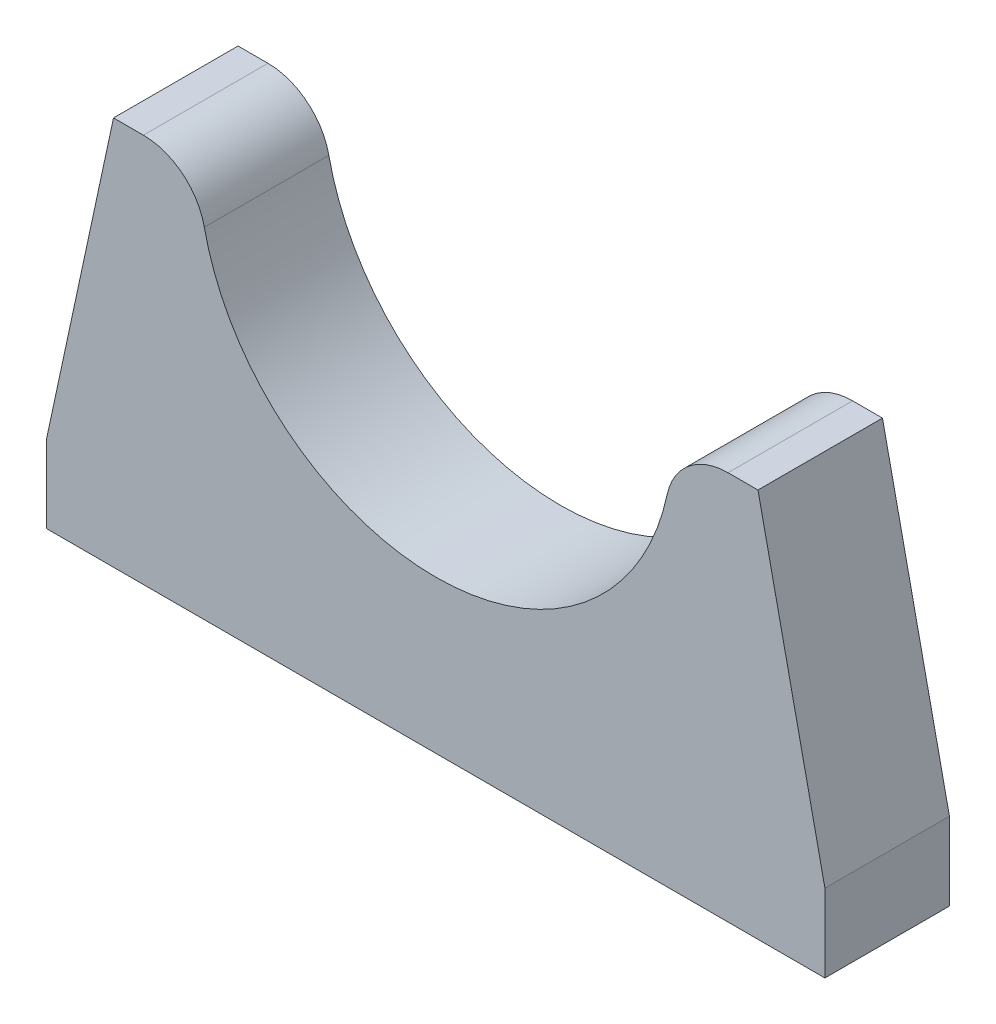
SolidWorks part; units mm, degrees
ref_plane "Plan de face" through (0, 0, 0) normal (0, 0, 1) x (1, 0, 0)
ref_plane "Plan de dessus" through (0, 0, 0) normal (0, 1, 0) x (1, 0, 0)
ref_plane "Plan de droite" through (0, 0, 0) normal (1, 0, 0) x (0, 0, -1)
sketch "Esquisse1" plane through (0, 0, 0) normal (0, 0, 1) x (1, 0, 0)
  line L0 (9.8, 25) -> (4.3, 25)
  line L1 (4.3, 25) -> (0, 5)
  line L2 (0, 5) -> (50, 5) construction
  line L3 (50, 5) -> (45.7, 25)
  line L4 (45.7, 25) -> (40.2, 25)
  line L5 (0, 5) -> (0, 0)
  line L6 (0, 0) -> (50, 0)
  line L7 (50, 0) -> (50, 5)
  line L8 (4.3, 25) -> (45.7, 25) construction
  arc A0 (9.8, 25) -> (40.2, 25) centre (25, 25) ccw
  point P0 (25, 25)
  dimension "D2" = 15.2
  dimension "D1" = 50
  dimension "D3" = 5.5
  dimension "D4" = 5.5
  dimension "D7" = 5
  dimension "D8" = 25
extrude "Boss.-Extru.1" add sketch "Esquisse1" along normal blind 8
fillet "Congé1" radius 4 2 edges at (40.2, 25, 4) (9.8, 25, 4)
sketch "Esquisse2" plane through (0, 0, 0) normal (0, -1, 0) x (1, 0, 0)
  line L0 (0, 4) -> (50, 4) construction
  line L1 (0, 8) -> (0, 0) construction
  line L2 (50, 8) -> (50, 0) construction
  line L3 (25, 0) -> (25, 8) construction
  line L4 (0, 0) -> (50, 0) construction
  line L5 (0, 8) -> (50, 8) construction
  circle A0 centre (5, 4) radius 1.25
  circle A1 centre (45, 4) radius 1.25
  dimension "D1" = 20
extrude "Enlèv. mat.-Extru.1" cut sketch "Esquisse2" against normal blind 8
